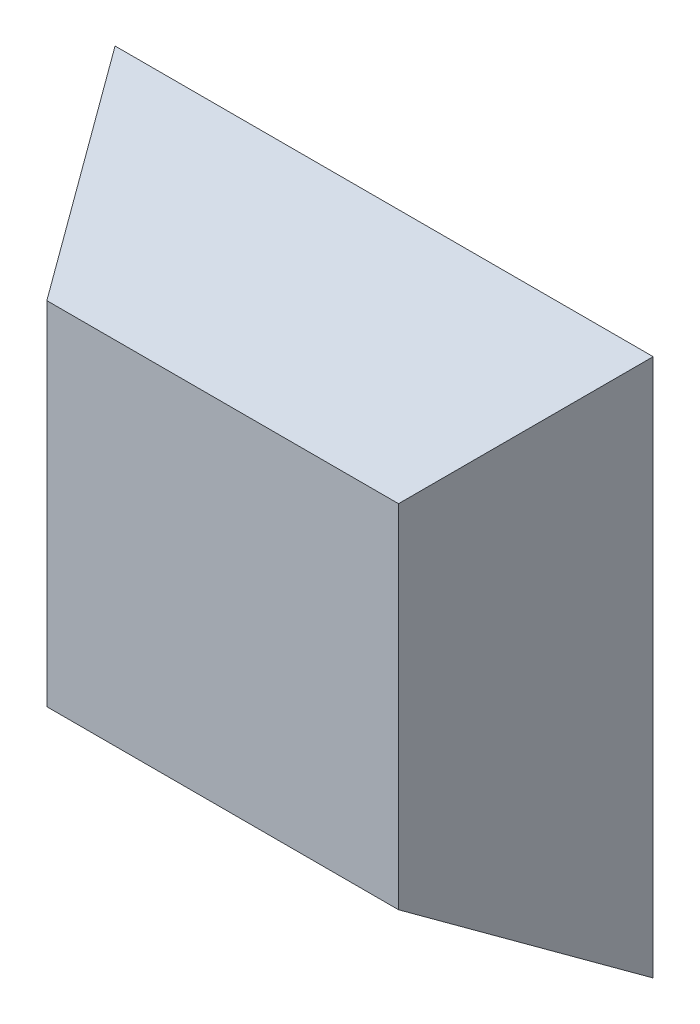
SolidWorks part; units mm, degrees
ref_plane "Front Plane" through (0, 0, 0) normal (0, 0, 1) x (1, 0, 0)
ref_plane "Top Plane" through (0, 0, 0) normal (0, 1, 0) x (1, 0, 0)
ref_plane "Right Plane" through (0, 0, 0) normal (1, 0, 0) x (0, 0, -1)
sketch "Sketch1" plane through (0, 0, 0) normal (0, 0, 1) x (1, 0, 0)
  line L1 (200, -200) -> (-200, -200)
  line L2 (200, -200) -> (200, 200)
  line L3 (200, 200) -> (-200, 200)
  line L4 (-200, -200) -> (-200, 200)
  line L5 (200, -200) -> (-200, 200) construction
  line L6 (200, 200) -> (-200, -200) construction
  point P0 (0, 0)
  dimension "D1" = 400
  dimension "D2" = 400
extrude "Boss-Extrude1" add sketch "Sketch1" along normal blind 120 draft 30
